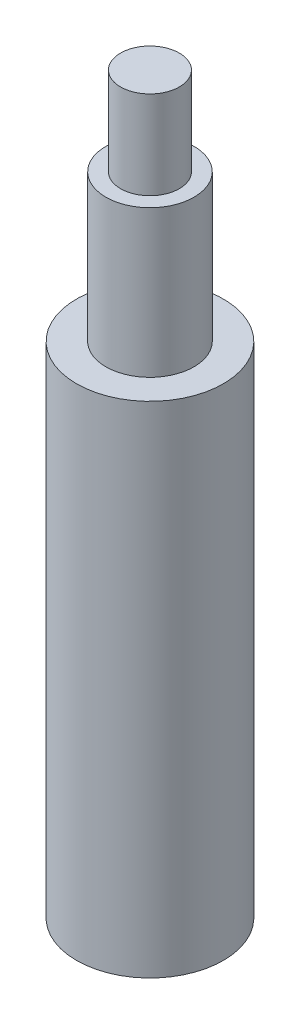
SolidWorks part; units mm, degrees
ref_plane "Front Plane" through (0, 0, 0) normal (0, 0, 1) x (1, 0, 0)
ref_plane "Top Plane" through (0, 0, 0) normal (0, 1, 0) x (1, 0, 0)
ref_plane "Right Plane" through (0, 0, 0) normal (1, 0, 0) x (0, 0, -1)
sketch3d "M4 Thread Blank Sketch datum points"
  point P0 (0, 140, 0)
  point P1 (10, 140, 0)
  point P2 (0, 140, -10)
ref_plane "M4 Thread Blank Sketch plane" through (0, 140, 0) normal (0, 1, 0) x (1, 0, 0)
sketch "M4 Thread Blank Sketch" plane through (0, 140, 0) normal (0, 1, 0) x (1, 0, 0)
  circle A0 centre (-20.2917, 0) radius 2
extrude "M4 Thread Blank" add sketch "M4 Thread Blank Sketch" against normal blind 6 separate body
sketch3d "Locating Spigot Sketch datum points"
  point P0 (0, 134, 0)
  point P1 (10, 134, 0)
  point P2 (0, 134, -10)
ref_plane "Locating Spigot Sketch plane" through (0, 134, 0) normal (0, 1, 0) x (1, 0, 0)
sketch "Locating Spigot Sketch" plane through (0, 134, 0) normal (0, 1, 0) x (1, 0, 0)
  circle A0 centre (-20.2917, 0) radius 3
extrude "Locating Spigot" add sketch "Locating Spigot Sketch" against normal blind 10
sketch3d "Guide Shoulder Sketch datum points"
  point P0 (0, 124, 0)
  point P1 (10, 124, 0)
  point P2 (0, 124, -10)
ref_plane "Guide Shoulder Sketch plane" through (0, 124, 0) normal (0, 1, 0) x (1, 0, 0)
sketch "Guide Shoulder Sketch" plane through (0, 124, 0) normal (0, 1, 0) x (1, 0, 0)
  circle A0 centre (-20.2917, 0) radius 5
extrude "Guide Shoulder" add sketch "Guide Shoulder Sketch" against normal blind 34
